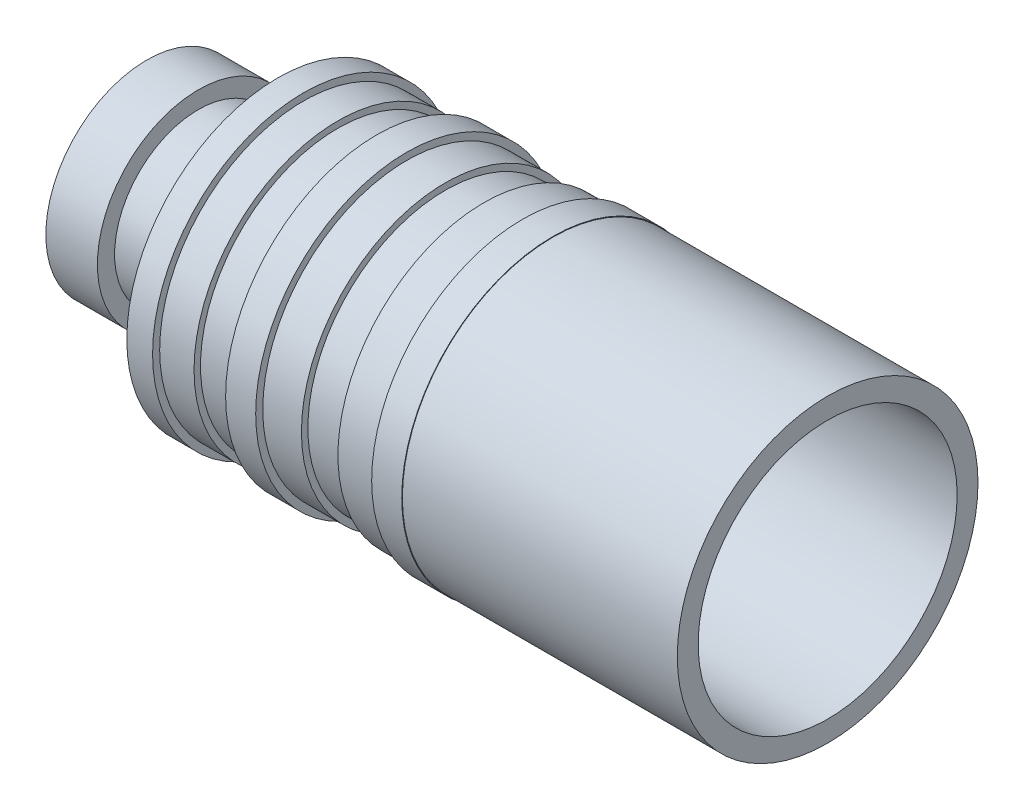
SolidWorks part; units mm, degrees
ref_plane "Front Plane" through (0, 0, 0) normal (0, 0, 1) x (1, 0, 0)
ref_plane "Top Plane" through (0, 0, 0) normal (0, 1, 0) x (1, 0, 0)
ref_plane "Right Plane" through (0, 0, 0) normal (1, 0, 0) x (0, 0, -1)
sketch "Sketch1" plane through (0, 0, 0) normal (1, 0, 0) x (0, 0, -1)
  circle A0 centre (0, 0) radius 15
  dimension "D1" = 30
extrude "Boss-Extrude1" add sketch "Sketch1" along normal blind 5.5
sketch "Sketch2" plane through (5.5, 0, 0) normal (1, 0, 0) x (0, 0, -1)
  circle A0 centre (0, 0) radius 23.5
  dimension "D1" = 47
extrude "Boss-Extrude2" add sketch "Sketch2" along normal blind 12
sketch "Sketch4" plane through (17.5, 0, 0) normal (1, 0, 0) x (0, 0, -1)
  circle A0 centre (0, 0) radius 19.5
  dimension "D1" = 39
extrude "Boss-Extrude3" add sketch "Sketch4" along normal blind 11.8
sketch "Sketch6" plane through (29.3, 0, 0) normal (1, 0, 0) x (0, 0, -1)
  circle A0 centre (0, 0) radius 20.25
  dimension "D1" = 40.5
extrude "Boss-Extrude4" add sketch "Sketch6" along normal blind 6.7 contours A0
sketch "Sketch7" plane through (36, 0, 0) normal (1, 0, 0) x (0, 0, -1)
  circle A0 centre (0, 0) radius 35.15
  dimension "D1" = 70.3
extrude "Boss-Extrude5" add sketch "Sketch7" along normal blind 6
sketch "Sketch8" plane through (42, 0, 0) normal (1, 0, 0) x (0, 0, -1)
  circle A0 centre (0, 0) radius 33.5
  dimension "D1" = 67
extrude "Boss-Extrude6" add sketch "Sketch8" along normal blind 8
sketch "Sketch9" plane through (50, 0, 0) normal (1, 0, 0) x (0, 0, -1)
  circle A0 centre (0, 0) radius 32
  dimension "D1" = 64
extrude "Boss-Extrude7" add sketch "Sketch9" along normal blind 9
sketch "Sketch10" plane through (59, 0, 0) normal (1, 0, 0) x (0, 0, -1)
  circle A0 centre (0, 0) radius 35.15
  dimension "D1" = 70.3
extrude "Boss-Extrude8" add sketch "Sketch10" along normal blind 7
sketch "Sketch11" plane through (66, 0, 0) normal (1, 0, 0) x (0, 0, -1)
  circle A0 centre (0, 0) radius 33.5
  dimension "D1" = 67
extrude "Boss-Extrude9" add sketch "Sketch11" along normal blind 9
sketch "Sketch12" plane through (75, 0, 0) normal (1, 0, 0) x (0, 0, -1)
  circle A0 centre (0, 0) radius 32
  dimension "D1" = 64
extrude "Boss-Extrude10" add sketch "Sketch12" along normal blind 9
sketch "Sketch13" plane through (84, 0, 0) normal (1, 0, 0) x (0, 0, -1)
  circle A0 centre (0, 0) radius 34
  dimension "D1" = 68
extrude "Boss-Extrude11" add sketch "Sketch13" along normal blind 9
sketch "Sketch14" plane through (93, 0, 0) normal (1, 0, 0) x (0, 0, -1)
  circle A0 centre (0, 0) radius 35.15
  dimension "D1" = 70.3
extrude "Boss-Extrude12" add sketch "Sketch14" along normal blind 7
sketch "Sketch15" plane through (100, 0, 0) normal (1, 0, 0) x (0, 0, -1)
  circle A0 centre (0, 0) radius 35
  dimension "D1" = 70
extrude "Boss-Extrude13" add sketch "Sketch15" along normal blind 64
sketch "Sketch16" plane through (0, 0, 0) normal (0, 1, 0) x (1, 0, 0)
  line L0 (164, 30.1458) -> (104.8757, 30.1458)
  line L1 (164, -35) -> (164, 35) construction
  line L2 (164, 30.1458) -> (164, 0)
  line L3 (164, 0) -> (113.5982, 0)
  spline S0 degree 3 poles (104.8757, 30.1458) (111.5752, 21.3238) (113.5982, 11.1159) (113.5982, 0) knots 0 0 0 0 1 1 1 1
revolve "Cut-Revolve1" cut sketch "Sketch16" angle 360 about L3
